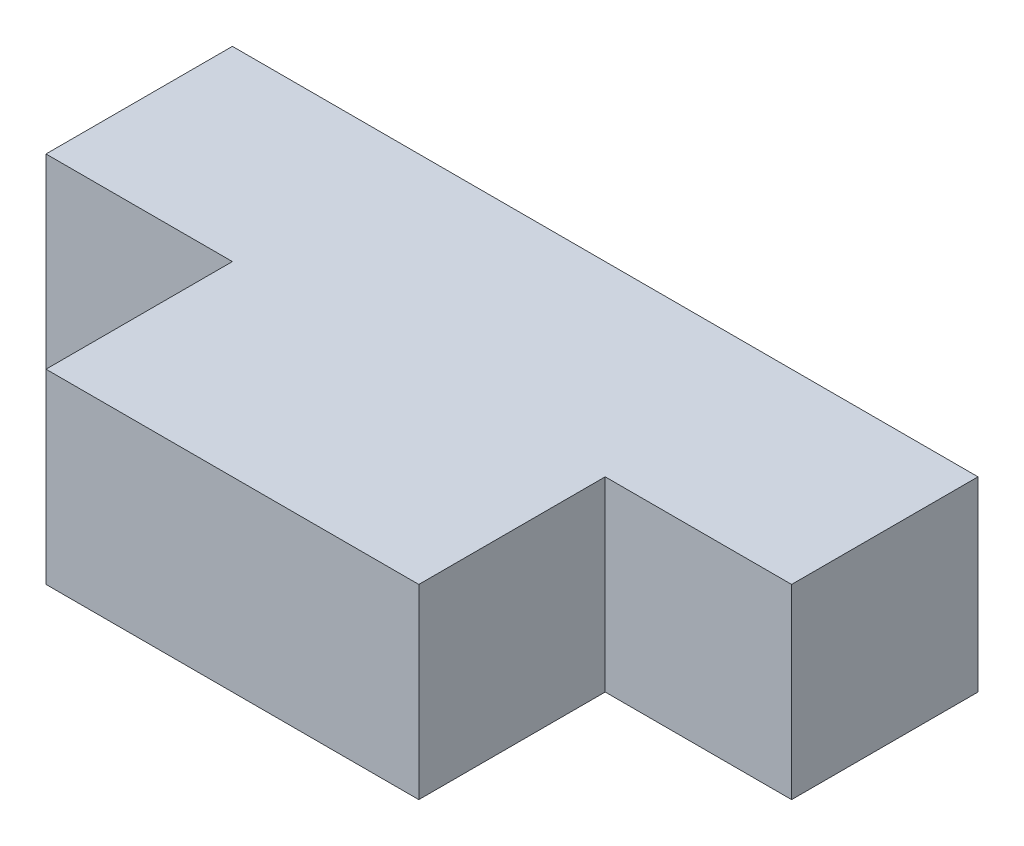
SolidWorks part; units mm, degrees
ref_plane "Спереди" through (0, 0, 0) normal (0, 0, 1) x (1, 0, 0)
ref_plane "Сверху" through (0, 0, 0) normal (0, 1, 0) x (1, 0, 0)
ref_plane "Справа" through (0, 0, 0) normal (1, 0, 0) x (0, 0, -1)
sketch "Sketch1" plane through (0, 0, 0) normal (0, 1, 0) x (1, 0, 0)
  line L0 (0, 0) -> (0, -5)
  line L1 (0, -5) -> (5, -5)
  line L2 (5, -5) -> (5, -10)
  line L3 (5, -10) -> (15, -10)
  line L4 (15, -10) -> (15, -5)
  line L5 (15, -5) -> (20, -5)
  line L6 (20, -5) -> (20, 0)
  line L7 (20, 0) -> (0, 0)
  dimension "D1" = 10
  dimension "D2" = 5
  dimension "D3" = 5
  dimension "D4" = 5
  dimension "D5" = 5
  dimension "D6" = 5
extrude "Boss-Extrude1" add sketch "Sketch1" along normal blind 5
